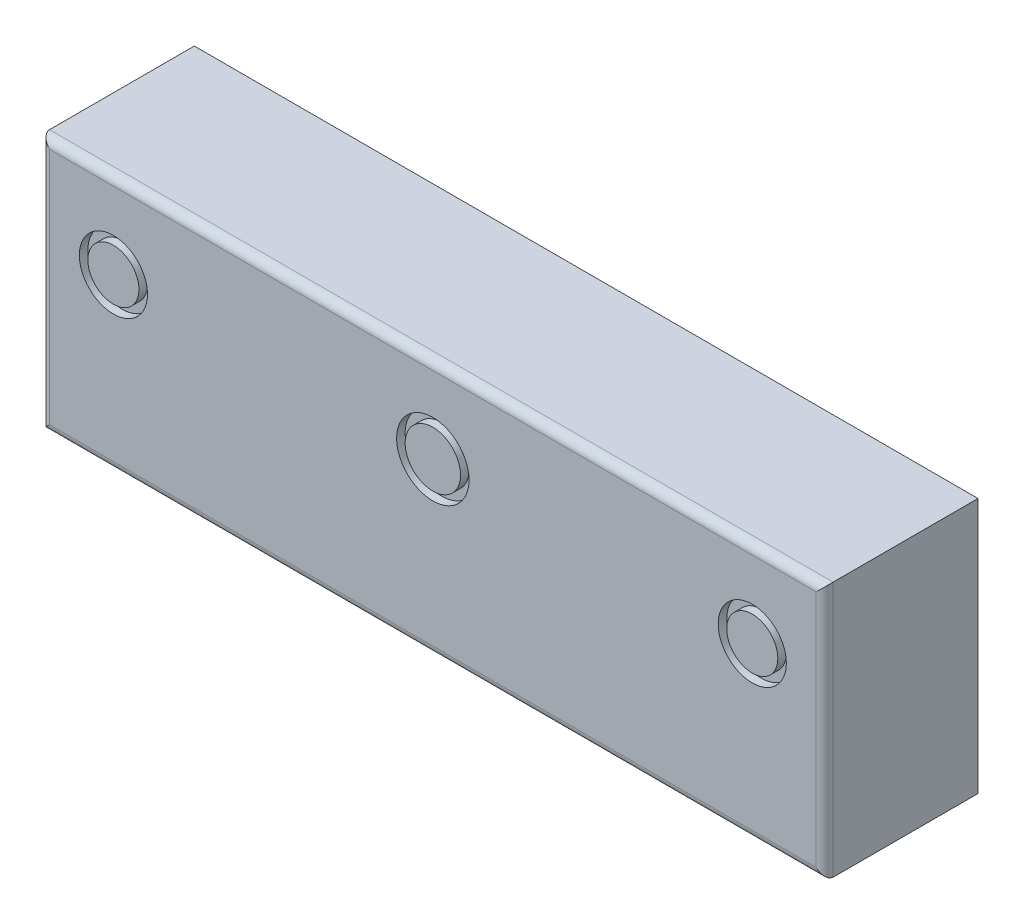
SolidWorks part; units mm, degrees
ref_plane "Front Plane" through (0, 0, 0) normal (0, 0, 1) x (1, 0, 0)
ref_plane "Top Plane" through (0, 0, 0) normal (0, 1, 0) x (1, 0, 0)
ref_plane "Right Plane" through (0, 0, 0) normal (1, 0, 0) x (0, 0, -1)
sketch "Sketch1" plane through (0, 0, 0) normal (0, 0, 1) x (1, 0, 0)
  line L1 (-46, -15) -> (46, -15)
  line L2 (-46, -15) -> (-46, 15)
  line L3 (-46, 15) -> (46, 15)
  line L4 (46, -15) -> (46, 15)
  line L5 (-46, -15) -> (46, 15) construction
  line L6 (-46, 15) -> (46, -15) construction
  point P0 (0, 0)
  dimension "D1" = 92
  dimension "D2" = 30
extrude "Boss-Extrude1" add sketch "Sketch1" along normal blind 18
sketch "Sketch2" plane through (0, 0, 18) normal (0, 0, 1) x (1, 0, 0)
  line L0 (-37.5, 5) -> (37.5, 5) construction
  circle A0 centre (0, 5) radius 3.25
  circle A1 centre (-37.5, 5) radius 3
  circle A2 centre (37.5, 5) radius 3
  circle A3 centre (-37.5, 5) radius 4
  circle A4 centre (0, 5) radius 4.25
  circle A5 centre (37.5, 5) radius 4
  point P2 (0, 5)
  dimension "D3" = 6
  dimension "D4" = 6
  dimension "D5" = 6.5
  dimension "D1" = 75
  dimension "D2" = 5
  dimension "D6" = 1
extrude "Cut-Extrude1" cut sketch "Sketch2" against normal blind 1
fillet "Fillet1" radius 1 4 edges at (-46, 0, 18) (0, -15, 18) (46, 0, 18) (0, 15, 18)
